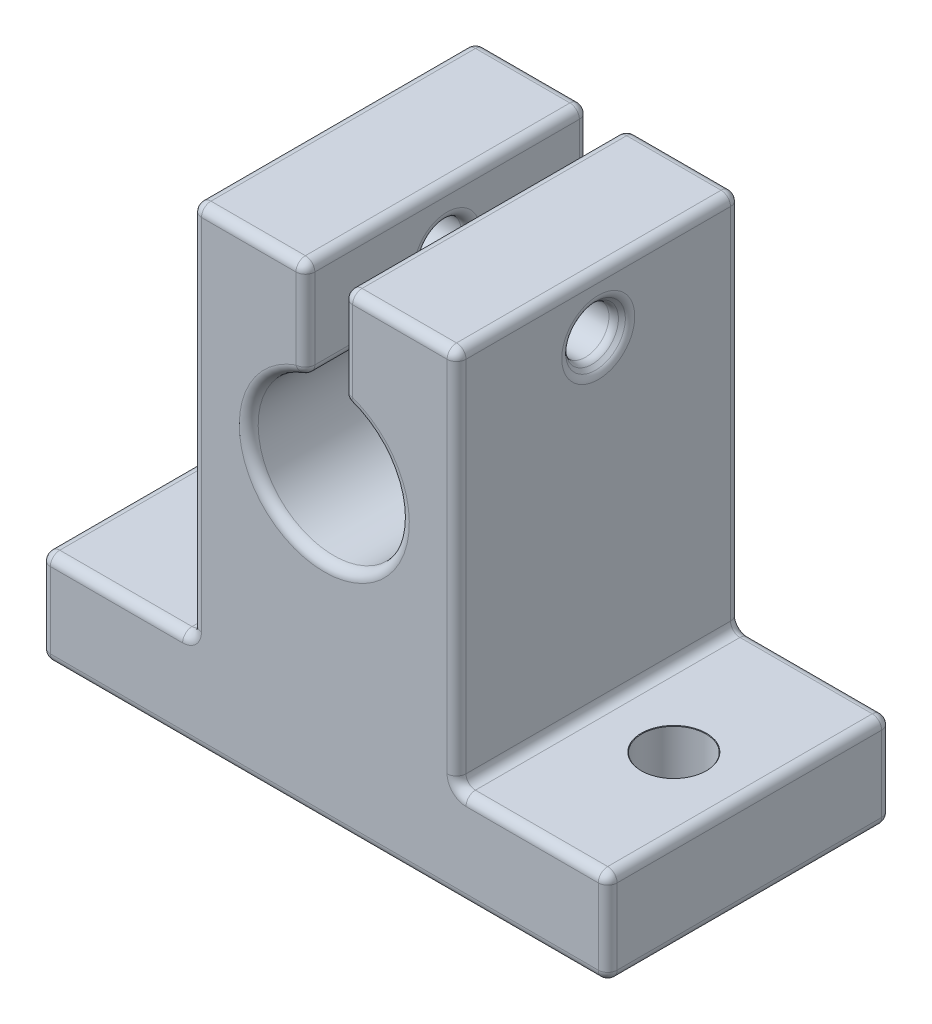
SolidWorks part; units mm, degrees
ref_plane "Front Plane" through (0, 0, 0) normal (0, 0, 1) x (1, 0, 0)
ref_plane "Top Plane" through (0, 0, 0) normal (0, 1, 0) x (1, 0, 0)
ref_plane "Right Plane" through (0, 0, 0) normal (1, 0, 0) x (0, 0, -1)
sketch "Sketch1" plane through (0, 0, 0) normal (0, 1, 0) x (1, 0, 0)
  line L1 (-15, 7.5) -> (15, 7.5)
  line L2 (-15, 7.5) -> (-15, -7.5)
  line L3 (-15, -7.5) -> (15, -7.5)
  line L4 (15, 7.5) -> (15, -7.5)
  line L5 (-15, 7.5) -> (15, -7.5) construction
  line L6 (-15, -7.5) -> (15, 7.5) construction
  point P0 (0, 0)
  dimension "D1" = 30
  dimension "D2" = 15
extrude "Boss-Extrude1" add sketch "Sketch1" along normal blind 5
sketch "Sketch2" plane through (0, 5, 0) normal (0, 1, 0) x (1, 0, 0)
  line L0 (0, 7.5) -> (0, -7.5) construction
  line L1 (15, 7.5) -> (-15, 7.5) construction
  line L2 (-15, -7.5) -> (15, -7.5) construction
  line L8 (-7, 7.5) -> (7, 7.5)
  line L9 (-7, 7.5) -> (-7, -7.5)
  line L10 (-7, -7.5) -> (7, -7.5)
  line L11 (7, 7.5) -> (7, -7.5)
  line L12 (-7, 7.5) -> (7, -7.5) construction
  line L13 (-7, -7.5) -> (7, 7.5) construction
  point P6 (0, 0)
  dimension "D1" = 14
extrude "Boss-Extrude2" add sketch "Sketch2" along normal blind 20
sketch "Sketch3" plane through (0, 0, 7.5) normal (0, 0, 1) x (1, 0, 0)
  line L0 (-7, 25) -> (7, 25) construction
  line L1 (-1, 30) -> (1, 30)
  line L2 (-1, 30) -> (-1, 19.873)
  line L4 (1, 30) -> (1, 19.873)
  line L5 (-1, 30) -> (1, 20) construction
  line L6 (-1, 20) -> (1, 30) construction
  arc A0 (-1, 19.873) -> (1, 19.873) centre (0, 16) ccw
  point P0 (0, 25)
  dimension "D3" = 8
  dimension "D1" = 2
extrude "Cut-Extrude1" cut sketch "Sketch3" against normal through all
hole_wizard "M3 Tapped Hole1" positions "3DSketch2" profile "Sketch5" tap size "M3" standard "AS"
sketch3d "3DSketch2"
  line L0 (7, 25, 0) -> (7, 23.3999, 0) construction
  line L1 (7, 25, 7.5) -> (7, 25, -7.5) construction
  point P0 (7, 22, 0)
  point P8 (0, 0, 0)
  dimension "D1" = 3
sketch "Sketch5" plane through (7, 22, 0) normal (0, 1, 0) x (0, 0, -1)
  line L0 (0, 0) -> (0, 12)
  line L1 (0, 12) -> (1.25, 11.2489)
  line L2 (1.25, 11.2489) -> (1.25, 0.475)
  line L3 (1.25, 0.475) -> (1.725, 0)
  line L5 (1.725, 0) -> (0, 0)
  line L6 (-1.25, 0.475) -> (-1.725, 0) construction
  line L10 (0, 12) -> (-1.25, 11.2489) construction
  line L11 (0, -6.35) -> (0, 107.95) construction
  dimension "Tap Drill Dia." = 2.5
  dimension "Tap Drill Depth" = 12
  dimension "Near C'Sink Dia." = 3.45
  dimension "Near C'Sink Angle" = 90
  dimension "Drill Angle" = 118
cosmetic thread "Hole Thread1" parameters "D1"=6, "D2"=3
fillet "Fillet1" radius 0.5 41 edges at (11, 5, -7.5) (15, 5, 0) (11, 5, 7.5) (7, 15, 7.5) (7, 25, 0) (7, 15, -7.5) (7, 5, 0) (7, 22, -1.725) (-1, 25, 0) (1, 25, 0) (15, 2.5, -7.5) (-15, 2.5, -7.5) (-15, 2.5, 7.5) (15, 2.5, 7.5) (-11, 5, 7.5) (-15, 5, 0) (-11, 5, -7.5) (0, 0, 7.5) (-15, 0, 0) (0, 0, -7.5) (15, 0, 0) (-7, 15, -7.5) (-7, 15, 7.5) (-4, 25, 7.5) (4, 25, 7.5) (-7, 25, 0) (4, 25, -7.5) (-4, 25, -7.5) (-7, 5, 0) (1, 19.873, 0) (-1, 19.873, 0) (1, 22.4365, -7.5) (0, 12, -7.5) (-1, 22.4365, -7.5) (1, 22.4365, 7.5) (0, 12, 7.5) (-1, 22.4365, 7.5) (1, 23.25, 0) (-1, 20.75, 0) (-4.2489, 22, -1.25) (6.525, 22, -1.25)
hole_wizard "M3 Clearance Hole1" positions "3DSketch3" profile "Sketch6" hole size "M3" standard "AS" end condition through all
sketch3d "3DSketch3"
  line L0 (14.5, 5, 0) -> (13.2067, 5, 0) construction
  line L2 (-15, 4.5, 7) -> (-15, 4.5, -7) construction
  point P0 (11, 5, 0)
  point P27 (-11.0314, 5, 0)
  point P30 (0, 0, 0)
  point P31 (0, 0, 0)
  point P32 (0, 0, 0)
  dimension "D1" = 4
  dimension "D2" = 4
sketch "Sketch6" plane through (11, 5, 0) normal (1, 0, 0) x (0, 0, 1)
  line L0 (0, 0) -> (0, 5)
  line L1 (0, 5) -> (1.7, 5)
  line L2 (1.7, 5) -> (1.7, 0.025)
  line L3 (1.7, 0.025) -> (1.725, 0)
  line L5 (1.725, 0) -> (0, 0)
  line L6 (-1.7, 0.025) -> (-1.725, 0) construction
  line L11 (0, -6.35) -> (0, 107.95) construction
  dimension "Thru Hole Dia." = 3.4
  dimension "Thru Hole Depth" = 5
  dimension "Near C'Sink Dia." = 3.45
  dimension "Near C'Sink Angle" = 90
